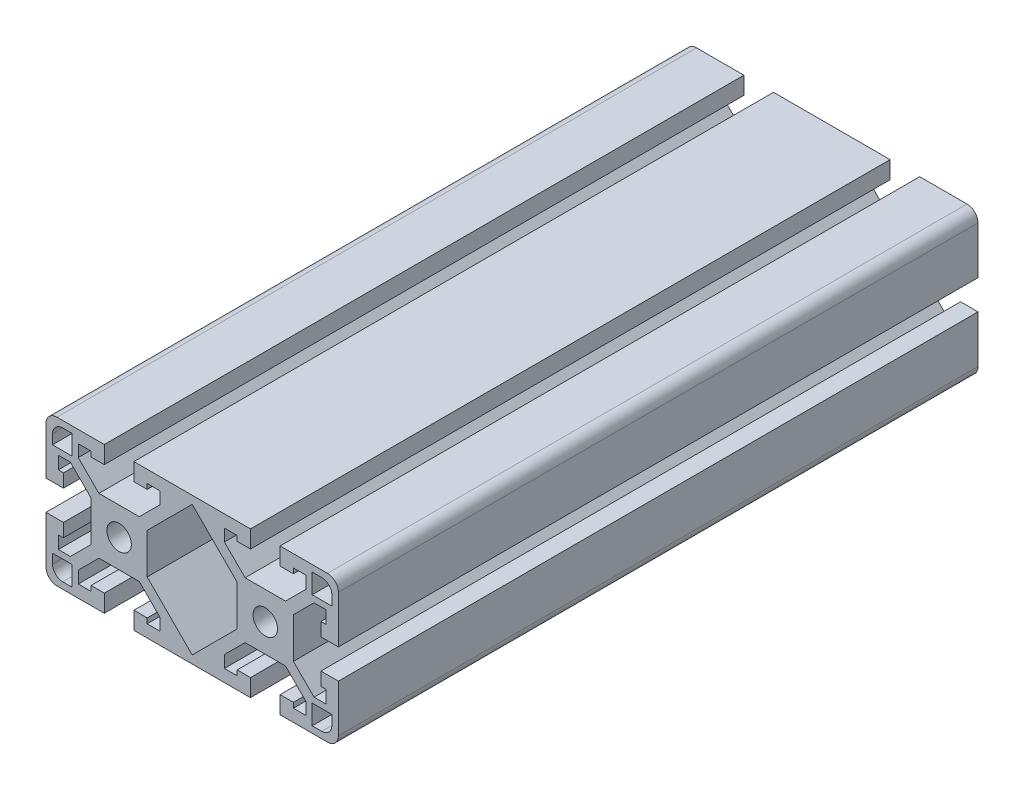
SolidWorks part; units mm, degrees
material "6063-T6"
ref_plane "Front Plane" through (0, 0, 0) normal (0, 0, 1) x (1, 0, 0)
ref_plane "Top Plane" through (0, 0, 0) normal (0, 1, 0) x (1, 0, 0)
ref_plane "Right Plane" through (0, 0, 0) normal (1, 0, 0) x (0, 0, -1)
sketch "Sketch1" plane through (0, 0, 0) normal (0, 1, 0) x (1, 0, 0)
  line L0 (0, 0) -> (0, -175)
  dimension "D1" = 175
other "40 series TS40-80LM-650037(1)"
ref_plane "Plane1" through (0, 0, 0) normal (0, 0, 1) x (0, 1, 0)
sketch "Sketch2" plane through (0, 0, 0) normal (0, 0, 1) x (0, 1, 0)
  line L2 (0, -27.681) -> (-5.5257, -27.681)
  line L3 (-5.5257, -27.681) -> (-11.176, -33.3313)
  line L4 (-7.6835, -36.6218) -> (-11.176, -36.6218)
  line L5 (-20, -37) -> (-20, -24.0488)
  line L6 (-4.0488, -40) -> (-17, -40)
  line L7 (-7.681, -20) -> (-7.681, -25.5257)
  line L8 (-7.681, -25.5257) -> (-13.3313, -31.176)
  line L9 (-16.6218, -31.176) -> (-16.6218, -27.6835)
  line L10 (-7.681, -14.4743) -> (-13.3313, -8.824)
  line L11 (-13.3313, -8.824) -> (-16.6218, -8.824)
  line L12 (-20, -24.0488) -> (-15.2248, -24.0488)
  line L13 (-20, 15.9512) -> (-20, -15.9512)
  line L14 (-5.5257, 12.319) -> (-17.8447, 0)
  line L15 (-5.5257, -12.319) -> (-17.8447, 0)
  line L16 (-7.681, -20) -> (-7.681, -14.4743)
  line L17 (-5.5257, -12.319) -> (0, -12.319)
  line L18 (7.681, -20) -> (7.681, -14.4743)
  line L19 (5.5257, -12.319) -> (17.8447, 0)
  line L20 (20, 15.9512) -> (15.2248, 15.9512)
  line L21 (4.0488, -35.2248) -> (7.6835, -35.2248)
  line L22 (7.681, 14.4743) -> (13.3313, 8.824)
  line L23 (7.6835, -36.6218) -> (7.6835, -35.2248)
  line L24 (4.0488, -35.2248) -> (4.0488, -40)
  line L25 (7.6835, -36.6218) -> (11.176, -36.6218)
  line L26 (11.176, -33.3313) -> (11.176, -36.6218)
  line L27 (7.681, -20) -> (7.681, -25.5257)
  line L28 (4.0488, -40) -> (17, -40)
  line L29 (20, -37) -> (20, -24.0488)
  line L30 (5.5257, -27.681) -> (11.176, -33.3313)
  line L31 (7.681, -25.5257) -> (13.3313, -31.176)
  line L32 (0, -12.319) -> (5.5257, -12.319)
  line L33 (0, -27.681) -> (5.5257, -27.681)
  line L35 (13.3313, 8.824) -> (16.6218, 8.824)
  line L36 (0, 12.319) -> (5.5257, 12.319)
  line L37 (-5.5257, 12.319) -> (0, 12.319)
  line L38 (16.6218, 8.824) -> (16.6218, 12.3165)
  line L39 (15.2248, 15.9512) -> (15.2248, 12.3165)
  line L40 (16.6218, 12.3165) -> (15.2248, 12.3165)
  line L41 (20, 24.0488) -> (15.2248, 24.0488)
  line L42 (0, 27.681) -> (5.5257, 27.681)
  line L43 (-4.0488, 40) -> (-17, 40)
  line L44 (-20, 37) -> (-20, 24.0488)
  line L45 (4.0488, 35.2248) -> (4.0488, 40)
  line L46 (16.6218, 31.176) -> (16.6218, 27.6835)
  line L47 (7.681, 20) -> (7.681, 25.5257)
  line L48 (13.3313, 31.176) -> (16.6218, 31.176)
  line L49 (15.2248, 24.0488) -> (15.2248, 27.6835)
  line L50 (7.681, 20) -> (7.681, 14.4743)
  line L51 (-7.681, 25.5257) -> (-7.681, 14.4743)
  line L52 (16.6218, 27.6835) -> (15.2248, 27.6835)
  line L53 (12.8372, 38.222) -> (12.8372, 32.8372)
  line L54 (20, 37) -> (20, 24.0488)
  line L55 (4.0488, 40) -> (17, 40)
  line L56 (12.8372, 38.222) -> (15.428, 38.222)
  line L57 (18.222, 35.428) -> (18.222, 32.8372)
  line L58 (12.8372, 32.8372) -> (18.222, 32.8372)
  line L59 (0, 27.681) -> (-5.5257, 27.681)
  line L60 (-4.0488, -35.2248) -> (-4.0488, -40)
  line L61 (-16.6218, -8.824) -> (-16.6218, -12.3165)
  line L62 (7.681, -14.4743) -> (13.3313, -8.824)
  line L63 (12.8372, -32.8372) -> (18.222, -32.8372)
  line L64 (20, 15.9512) -> (20, -15.9512)
  line L65 (7.681, 25.5257) -> (13.3313, 31.176)
  line L66 (5.5257, 27.681) -> (11.176, 33.3313)
  line L67 (5.5257, 12.319) -> (17.8447, 0)
  line L68 (-13.3313, -31.176) -> (-16.6218, -31.176)
  line L69 (-11.176, -33.3313) -> (-11.176, -36.6218)
  line L70 (-15.2248, -15.9512) -> (-15.2248, -12.3165)
  line L71 (-12.8372, -38.222) -> (-12.8372, -32.8372)
  line L72 (-12.8372, -38.222) -> (-15.428, -38.222)
  line L73 (-15.2248, -24.0488) -> (-15.2248, -27.6835)
  line L74 (-16.6218, -27.6835) -> (-15.2248, -27.6835)
  line L75 (-18.222, -35.428) -> (-18.222, -32.8372)
  line L76 (-12.8372, -32.8372) -> (-18.222, -32.8372)
  line L77 (-7.6835, -36.6218) -> (-7.6835, -35.2248)
  line L78 (-4.0488, -35.2248) -> (-7.6835, -35.2248)
  line L79 (-20, -15.9512) -> (-15.2248, -15.9512)
  line L80 (-16.6218, -12.3165) -> (-15.2248, -12.3165)
  line L81 (18.222, -35.428) -> (18.222, -32.8372)
  line L82 (12.8372, -38.222) -> (15.428, -38.222)
  line L83 (12.8372, -38.222) -> (12.8372, -32.8372)
  line L84 (16.6218, -12.3165) -> (15.2248, -12.3165)
  line L85 (20, -15.9512) -> (15.2248, -15.9512)
  line L86 (16.6218, -27.6835) -> (15.2248, -27.6835)
  line L87 (15.2248, -24.0488) -> (15.2248, -27.6835)
  line L88 (15.2248, -15.9512) -> (15.2248, -12.3165)
  line L89 (13.3313, -31.176) -> (16.6218, -31.176)
  line L90 (16.6218, -8.824) -> (16.6218, -12.3165)
  line L91 (20, -24.0488) -> (15.2248, -24.0488)
  line L92 (13.3313, -8.824) -> (16.6218, -8.824)
  line L93 (16.6218, -31.176) -> (16.6218, -27.6835)
  line L94 (11.176, 33.3313) -> (11.176, 36.6218)
  line L95 (7.6835, 36.6218) -> (11.176, 36.6218)
  line L96 (7.6835, 36.6218) -> (7.6835, 35.2248)
  line L97 (4.0488, 35.2248) -> (7.6835, 35.2248)
  line L98 (-4.0488, 35.2248) -> (-4.0488, 40)
  line L99 (-4.0488, 35.2248) -> (-7.6835, 35.2248)
  line L100 (-7.6835, 36.6218) -> (-7.6835, 35.2248)
  line L101 (-7.6835, 36.6218) -> (-11.176, 36.6218)
  line L102 (-11.176, 33.3313) -> (-11.176, 36.6218)
  line L103 (-5.5257, 27.681) -> (-11.176, 33.3313)
  line L104 (-18.222, 35.428) -> (-18.222, 32.8372)
  line L105 (-12.8372, 32.8372) -> (-18.222, 32.8372)
  line L106 (-7.681, 25.5257) -> (-13.3313, 31.176)
  line L107 (-13.3313, 31.176) -> (-16.6218, 31.176)
  line L108 (-16.6218, 31.176) -> (-16.6218, 27.6835)
  line L109 (-7.681, 14.4743) -> (-13.3313, 8.824)
  line L110 (-16.6218, 12.3165) -> (-15.2248, 12.3165)
  line L111 (-20, 15.9512) -> (-15.2248, 15.9512)
  line L112 (-15.2248, 15.9512) -> (-15.2248, 12.3165)
  line L113 (-16.6218, 8.824) -> (-16.6218, 12.3165)
  line L114 (-13.3313, 8.824) -> (-16.6218, 8.824)
  line L115 (-16.6218, 27.6835) -> (-15.2248, 27.6835)
  line L116 (-15.2248, 24.0488) -> (-15.2248, 27.6835)
  line L117 (-20, 24.0488) -> (-15.2248, 24.0488)
  line L118 (-12.8372, 38.222) -> (-15.428, 38.222)
  line L119 (-12.8372, 38.222) -> (-12.8372, 32.8372)
  arc A0 (-20, -37) -> (-17, -40) centre (-17, -37) ccw
  arc A1 (-20, 37) -> (-17, 40) centre (-17, 37) cw
  arc A2 (20, 37) -> (17, 40) centre (17, 37) ccw
  arc A3 (-15.428, -38.222) -> (-18.222, -35.428) centre (-15.428, -35.428) cw
  arc A4 (15.428, -38.222) -> (18.222, -35.428) centre (15.428, -35.428) ccw
  arc A5 (15.428, 38.222) -> (18.222, 35.428) centre (15.428, 35.428) cw
  arc A6 (-15.428, 38.222) -> (-18.222, 35.428) centre (-15.428, 35.428) ccw
  arc A7 (20, -37) -> (17, -40) centre (17, -37) cw
  circle A8 centre (0, -20) radius 3.35
  circle A9 centre (0, 20) radius 3.35
  point P1 (-20, 20)
  point P3 (-20, 40)
  point P34 (-20, 0)
  point P51 (20, 0)
  point P76 (0, 40)
  point P77 (20, 40)
  point P143 (20, 20)
  point P144 (20, -20)
  point P145 (-20, -20)
  point P146 (-20, -40)
  point P147 (0, -40)
  point P148 (20, -40)
  point P149 (0, 0)
  dimension "D1" = 6.7
hole_wizard "M8x1.25 Tapped Hole1" positions "Sketch3" profile "Sketch4" tap size "M8x1.25" standard "ANSI Metric"
sketch "Sketch3" plane through (0, 0, 0) normal (0, 0, -1) x (-1, 0, 0)
  point P0 (-20, 0)
  point P3 (20, 0)
sketch "Sketch4" plane through (20, 0, 0) normal (1, 0, 0) x (0, 1, 0)
  line L0 (0, 0) -> (0, 32.0429)
  line L1 (0, 32.0429) -> (3.4, 30)
  line L2 (3.4, 30) -> (3.4, 0)
  line L5 (3.4, 0) -> (0, 0)
  line L10 (0, 32.0429) -> (-3.4, 30) construction
  line L11 (0, -6.35) -> (0, 107.95) construction
  dimension "Tap Drill Dia." = 6.8
  dimension "Tap Drill Depth" = 30
  dimension "Drill Angle" = 118
cosmetic thread "Hole Thread1"
cosmetic thread "Hole Thread2"
